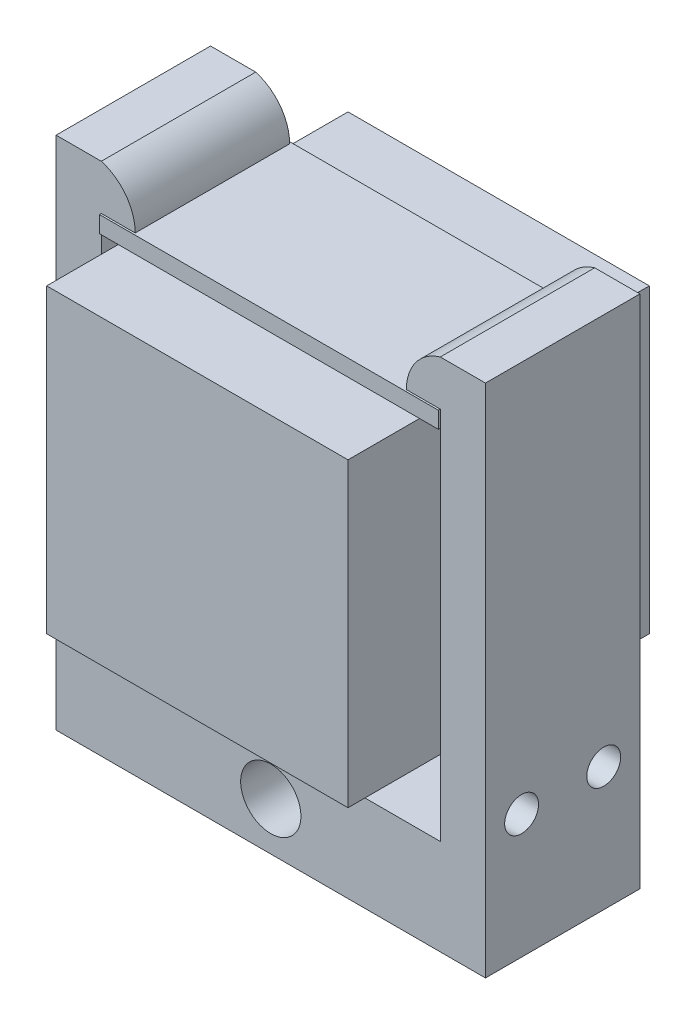
SolidWorks part; units mm, degrees
ref_plane "Front Plane" through (0, 0, 0) normal (0, 0, 1) x (1, 0, 0)
ref_plane "Top Plane" through (0, 0, 0) normal (0, 1, 0) x (1, 0, 0)
ref_plane "Right Plane" through (0, 0, 0) normal (1, 0, 0) x (0, 0, -1)
sketch "Sketch1" plane through (0, 0, 0) normal (0, 1, 0) x (1, 0, 0)
  line L9 (-22.5, -10.5) -> (22.5, -10.5)
  line L10 (-22.5, -10.5) -> (-22.5, 10.5)
  line L11 (-22.5, 10.5) -> (22.5, 10.5)
  line L12 (22.5, -10.5) -> (22.5, 10.5)
  line L13 (-22.5, -10.5) -> (22.5, 10.5) construction
  line L14 (-22.5, 10.5) -> (22.5, -10.5) construction
  point P0 (0, 0)
  point P7 (0, 0)
  dimension "D2" = 21
  dimension "D3" = 45
extrude "Boss-Extrude1" add sketch "Sketch1" along normal blind 2.2
sketch "Sketch2" plane through (0, 0, 0) normal (0, 1, 0) x (1, 0, 0)
  line L1 (-20, -20) -> (20, -20)
  line L2 (-20, -20) -> (-20, 20)
  line L3 (-20, 20) -> (20, 20)
  line L4 (20, -20) -> (20, 20)
  line L5 (-20, -20) -> (20, 20) construction
  line L6 (-20, 20) -> (20, -20) construction
  point P0 (0, 0)
  dimension "D1" = 40
  dimension "D2" = 40
extrude "Boss-Extrude2" add sketch "Sketch2" against normal blind 40 separate body
sketch "Sketch3" plane through (0, 0, 0) normal (0, 0, 1) x (1, 0, 0)
  line L1 (-22.5, -60.2) -> (22.5, -60.2)
  line L2 (-22.5, -60.2) -> (-22.5, -47.5)
  line L3 (-22.5, -47.5) -> (22.5, -47.5)
  line L4 (22.5, -60.2) -> (22.5, -47.5)
  line L5 (-22.5, -60.2) -> (22.5, -47.5) construction
  line L6 (-22.5, -47.5) -> (22.5, -60.2) construction
  line L7 (22.5, 2.2) -> (22.5, 0) construction
  line L8 (0, -22) -> (0, 22) construction
  line L9 (-22.5, 0) -> (22.5, 0) construction
  line L10 (22.5, -60.2) -> (28.5, -60.2)
  line L11 (22.5, -60.2) -> (22.5, 0)
  line L13 (28.5, -60.2) -> (28.5, 0)
  line L16 (-28.5, -60.2) -> (-28.5, 0)
  line L17 (-22.5, -60.2) -> (-28.5, -60.2)
  line L18 (-22.5, -60.2) -> (-22.5, 0)
  line L20 (22.5, -47.5) -> (22.5, 0) construction
  line L21 (22, 0) -> (-22, 0) construction
  line L22 (28.5, 0) -> (28.5, 8.2)
  line L23 (28.5, 0) -> (28.5, 5.5196) construction
  line L24 (28.5, 8.2) -> (22.5, 8.2)
  line L26 (22.5, 0) -> (22.5, 2.2)
  line L27 (18, 2.2) -> (22.5, 2.2)
  line L28 (-22.5, 0) -> (-22.5, 2.2)
  line L29 (-18, 2.2) -> (-22.5, 2.2)
  line L30 (-28.5, 0) -> (-28.5, 8.2)
  line L31 (-28.5, 8.2) -> (-22.5, 8.2)
  line L32 (0, -40) -> (0, -47.5) construction
  line L33 (-20, -40) -> (20, -40) construction
  line L34 (-22.5, -43.75) -> (22.5, -43.75) construction
  line L36 (-22.5, -46) -> (22.5, -46) construction
  line L37 (-22.5, -46) -> (-22.5, -41.5) construction
  line L38 (-22.5, -41.5) -> (22.5, -41.5) construction
  line L39 (22.5, -46) -> (22.5, -41.5) construction
  line L40 (-22.5, -46) -> (22.5, -41.5) construction
  line L41 (-22.5, -41.5) -> (22.5, -46) construction
  circle A2 centre (0, -53.85) radius 4
  arc A3 (22.5, 8.2) -> (18, 2.2) centre (24.25, 2.2) ccw
  arc A4 (-22.5, 8.2) -> (-18, 2.2) centre (-24.25, 2.2) cw
  point P0 (0, -53.85)
  point P39 (0, -43.75)
  point P40 (0, -43.75)
  point P45 (0, 0)
  dimension "D8" = 8
  dimension "D2" = 12.7
  dimension "D7" = 6
  dimension "D9" = 0
  dimension "D4" = 8.2
  dimension "D5" = 0
  dimension "D6" = 4.5
  dimension "D10" = 2.2
  dimension "D3" = 4.5
  dimension "D11" = 1.5
extrude "SnapFit-41mm_spacing-4mm_width" add sketch "Sketch3" along normal mid plane 20.5 separate body
sketch "Sketch4" plane through (28.5, 0, 0) normal (1, 0, 0) x (0, 0, -1)
  line L0 (0, 31.35) -> (0, -31.35) construction
  line L4 (-10.25, -60.2) -> (-10.25, 8.2) construction
  circle A0 centre (-5.45, -43.75) radius 2.25
  circle A1 centre (5.45, -43.75) radius 2.25
  circle A2 centre (-5.45, -43.75) radius 3.8 construction
  dimension "D1" = 4.5
  dimension "D2" = 7.6
  dimension "D3" = 1
extrude "Cut-Extrude1" cut sketch "Sketch4" against normal through all
sketch "Sketch5" plane through (-28.5, 0, 0) normal (-1, 0, 0) x (0, 0, 1)
  line L0 (-5.45, -39.92) -> (-5.45, -47.58) construction
  line L1 (-2.1331, -45.665) -> (-8.7669, -41.835) construction
  line L2 (-8.7669, -45.665) -> (-2.1331, -41.835) construction
  line L3 (-8.7669, -41.835) -> (-8.7669, -45.665)
  line L4 (-5.45, -39.92) -> (-8.7669, -41.835)
  line L5 (-2.1331, -41.835) -> (-5.45, -39.92)
  line L6 (-2.1331, -45.665) -> (-2.1331, -41.835)
  line L7 (-5.45, -47.58) -> (-2.1331, -45.665)
  line L8 (-8.7669, -45.665) -> (-5.45, -47.58)
  line L9 (0, -31.35) -> (0, 31.35) construction
  line L10 (8.7669, -45.665) -> (2.1331, -41.835) construction
  line L11 (2.1331, -45.665) -> (8.7669, -41.835) construction
  line L12 (5.45, -39.92) -> (5.45, -47.58) construction
  line L13 (8.7669, -45.665) -> (5.45, -47.58)
  line L14 (5.45, -47.58) -> (2.1331, -45.665)
  line L15 (2.1331, -45.665) -> (2.1331, -41.835)
  line L16 (2.1331, -41.835) -> (5.45, -39.92)
  line L17 (5.45, -39.92) -> (8.7669, -41.835)
  line L18 (8.7669, -41.835) -> (8.7669, -45.665)
  circle A0 centre (-5.45, -43.75) radius 3.83 construction
  circle A1 centre (-5.45, -43.75) radius 2.25 construction
  circle A2 centre (5.45, -43.75) radius 3.83 construction
  point P12 (-5.45, -43.75)
  point P23 (-5.45, -43.75)
  point P26 (5.45, -43.75)
  point P27 (5.45, -43.75)
  dimension "D1" = 7.66
  dimension "D2" = 3
  dimension "D3" = 6
extrude "BoltClampP-width_6mm" cut sketch "Sketch5" against normal blind 3
other "Save Bodies1"
equation "\"D5@Sketch3\"=\"D9@Sketch3\""
